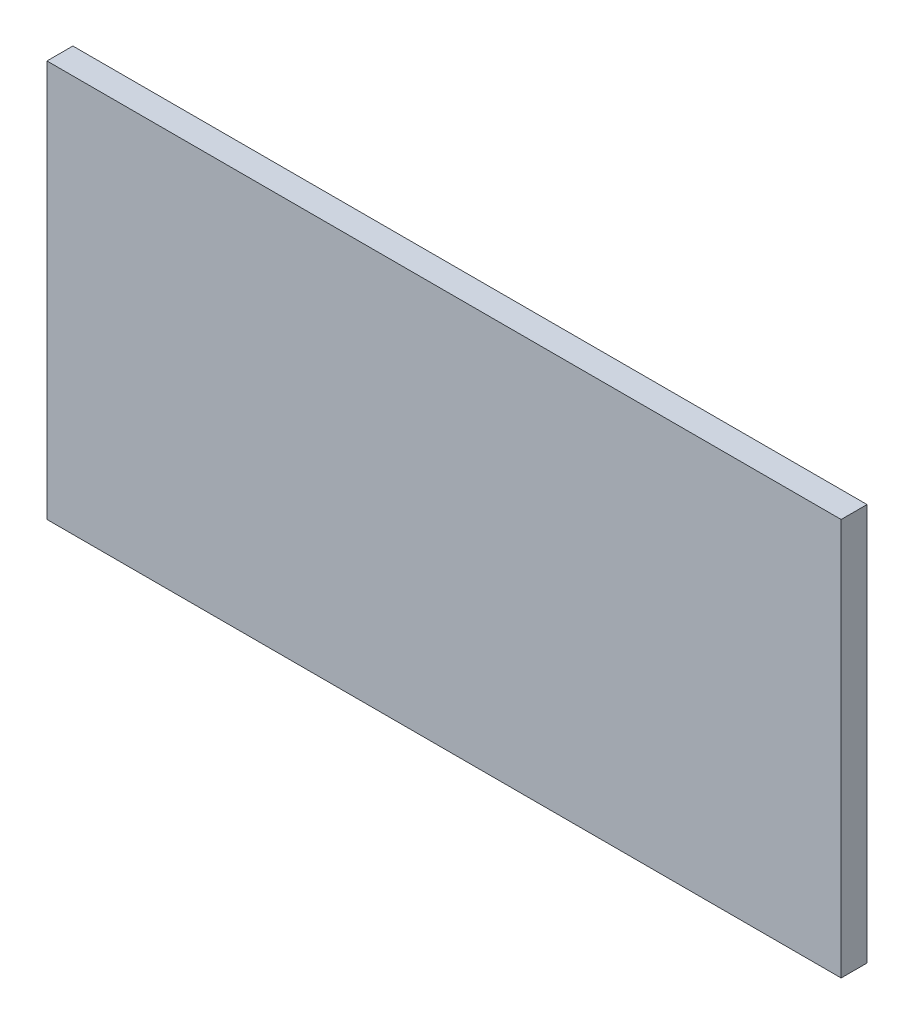
SolidWorks part; units mm, degrees
ref_plane "Front Plane" through (0, 0, 0) normal (0, 0, 1) x (1, 0, 0)
ref_plane "Top Plane" through (0, 0, 0) normal (0, 1, 0) x (1, 0, 0)
ref_plane "Right Plane" through (0, 0, 0) normal (1, 0, 0) x (0, 0, -1)
sketch "Sketch1" plane through (0, 0, 0) normal (0, 0, 1) x (1, 0, 0)
  line L1 (-46, 23) -> (46, 23)
  line L2 (-46, 23) -> (-46, -23)
  line L3 (-46, -23) -> (46, -23)
  line L4 (46, 23) -> (46, -23)
  line L5 (-46, 23) -> (46, -23) construction
  line L6 (-46, -23) -> (46, 23) construction
  point P0 (0, 0)
  dimension "D1" = 92
  dimension "D2" = 46
extrude "Boss-Extrude1" add sketch "Sketch1" along normal blind 3
